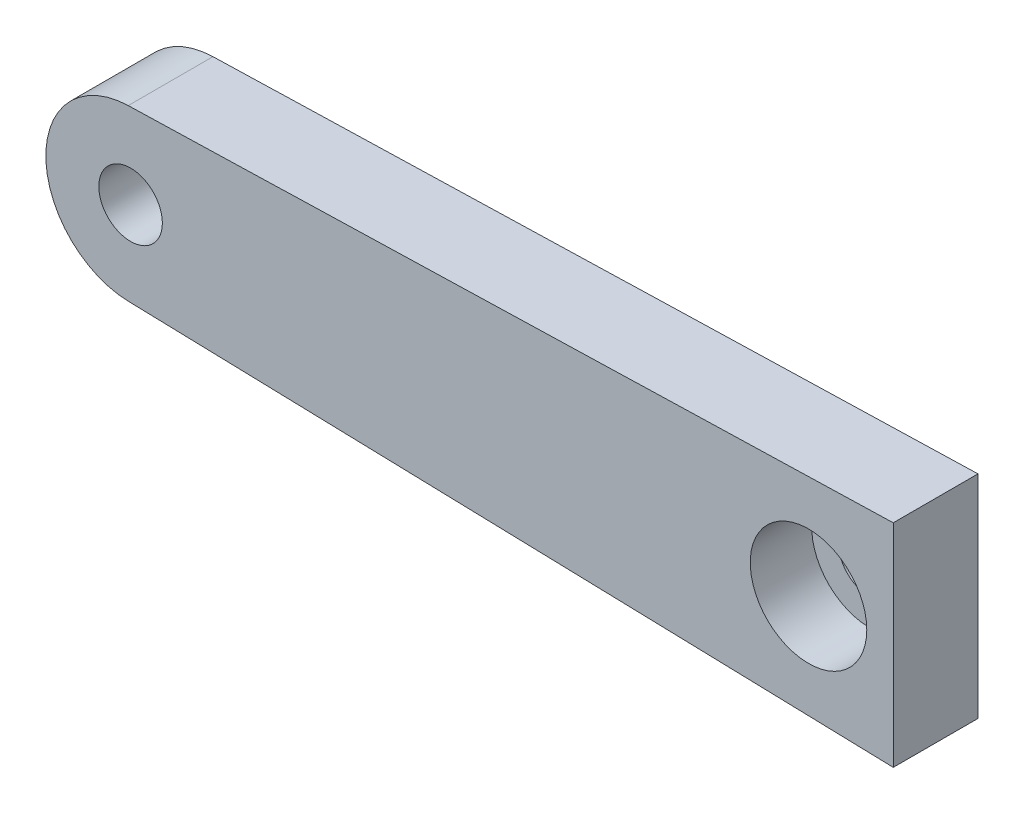
SolidWorks part; units mm, degrees
ref_plane "前视基准面" through (0, 0, 0) normal (0, 0, 1) x (1, 0, 0)
ref_plane "上视基准面" through (0, 0, 0) normal (0, 1, 0) x (1, 0, 0)
ref_plane "右视基准面" through (0, 0, 0) normal (1, 0, 0) x (0, 0, -1)
sketch "草图1" plane through (0, 0, 0) normal (0, 0, 1) x (1, 0, 0)
  line L0 (-32.1109, 3.9985) -> (4, 5)
  line L1 (4, 5) -> (4, -5)
  line L2 (-20.1052, 0) -> (7.7792, 0) construction
  line L3 (-32.1109, -3.9985) -> (4, -5)
  circle A0 centre (0, 0) radius 1.5
  circle A1 centre (-32, 0) radius 1.5
  arc A2 (-32.1109, 3.9985) -> (-32.1109, -3.9985) centre (-32, 0) ccw
  point P12 (4, 0)
  dimension "D1" = 3
  dimension "D2" = 3
  dimension "D3" = 32
  dimension "D7" = 4
  dimension "D4" = 5
  dimension "D6" = 4
extrude "凸台-拉伸1" add sketch "草图1" along normal blind 4
sketch "草图2" plane through (0, 0, 4) normal (0, 0, 1) x (1, 0, 0)
  circle A0 centre (0, 0) radius 2.75
  dimension "D1" = 5.5
extrude "切除-拉伸1" cut sketch "草图2" against normal blind 2.9
